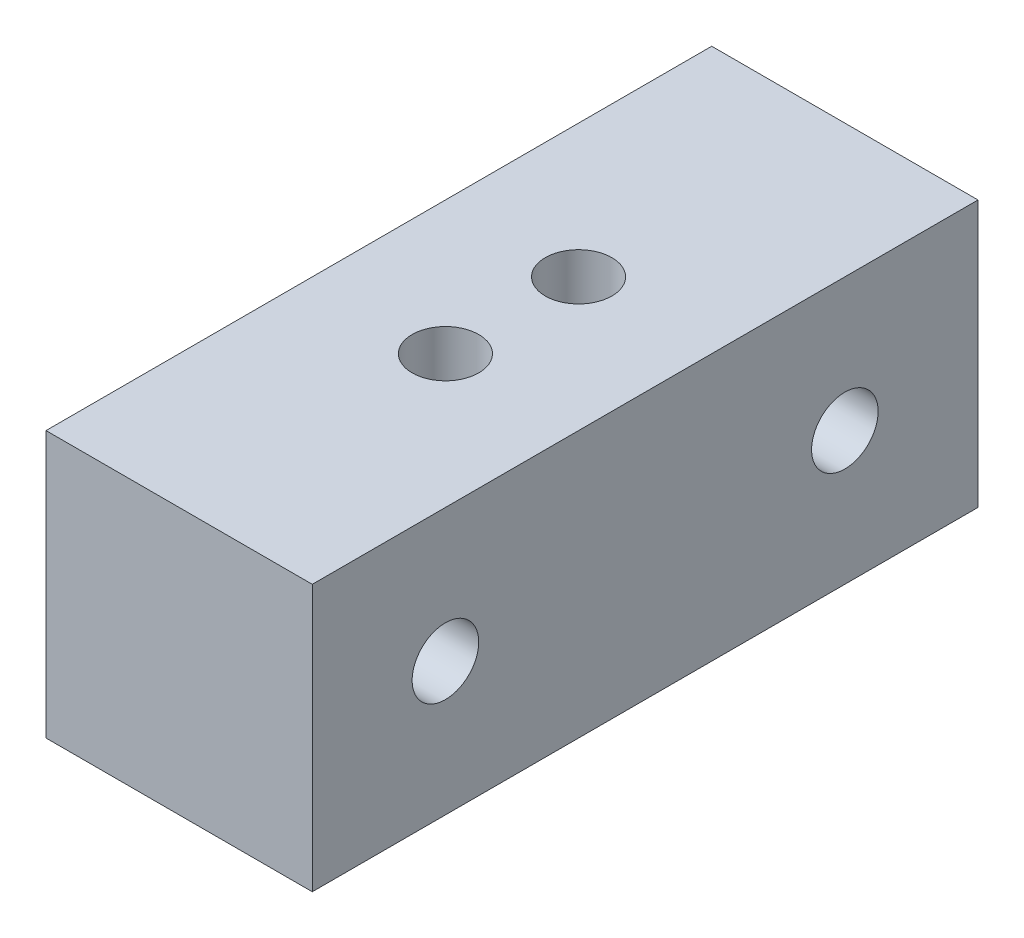
SolidWorks part; units mm, degrees
material "6061-T6 (SS)"
ref_plane "前视基准面" through (0, 0, 0) normal (0, 0, 1) x (1, 0, 0)
ref_plane "上视基准面" through (0, 0, 0) normal (0, 1, 0) x (1, 0, 0)
ref_plane "右视基准面" through (0, 0, 0) normal (1, 0, 0) x (0, 0, -1)
other "Configuration Table"
sketch "草图1" plane through (0, 0, 0) normal (0, 0, 1) x (1, 0, 0)
  line L0 (0, 0) -> (20, 0)
  line L1 (20, 0) -> (20, 20)
  line L2 (20, 20) -> (0, 20)
  line L3 (0, 20) -> (0, 0)
extrude "凸台-拉伸1" add sketch "草图1" along normal blind 50
sketch "草图2" plane through (20, 0, 0) normal (1, 0, 0) x (0, 0, -1)
  circle A0 centre (-10, 10) radius 2.5
  circle A1 centre (-40, 10) radius 2.5
extrude "切除-拉伸1" cut sketch "草图2" against normal blind 14
sketch "草图3" plane through (0, 20, 0) normal (0, 1, 0) x (1, 0, 0)
  circle A0 centre (10, -20) radius 2.5
  circle A1 centre (10, -30) radius 2.5
extrude "切除-拉伸2" cut sketch "草图3" against normal blind 14
